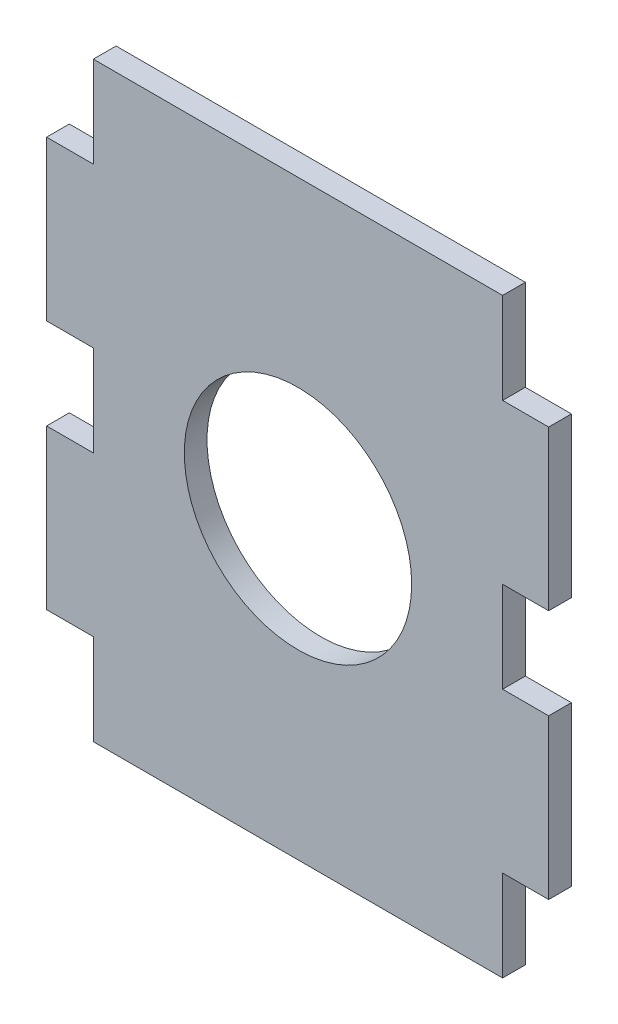
SolidWorks part; units mm, degrees
ref_plane "Front Plane" through (0, 0, 0) normal (0, 0, 1) x (1, 0, 0)
ref_plane "Top Plane" through (0, 0, 0) normal (0, 1, 0) x (1, 0, 0)
ref_plane "Right Plane" through (0, 0, 0) normal (1, 0, 0) x (0, 0, -1)
sketch "Sketch1" plane through (0, 0, 0) normal (0, 0, 1) x (1, 0, 0)
  line L1 (-56.6738, 356.0789) -> (0.4762, 356.0789)
  line L2 (-63.2032, 343.3789) -> (-63.2032, 321.1539)
  line L3 (-56.6738, 273.5289) -> (0.4762, 273.5289)
  line L4 (6.9085, 343.3789) -> (6.9085, 321.1539)
  line L6 (-56.6738, 347.6447) -> (-56.6738, 243.0666) construction
  line L7 (-63.2032, 308.4539) -> (-63.2032, 286.2289)
  line L8 (6.9085, 308.4539) -> (6.9085, 286.2289)
  line L9 (-63.2032, 343.3789) -> (-56.6738, 343.3789)
  line L10 (-56.6738, 356.0789) -> (-56.6738, 343.3789)
  line L11 (0.4762, 243.0666) -> (0.4762, 347.6447) construction
  line L14 (-63.2032, 286.2289) -> (-56.6738, 286.2289)
  line L15 (-56.6738, 273.5289) -> (-56.6738, 286.2289)
  line L16 (-63.2032, 308.4539) -> (-56.6738, 308.4539)
  line L18 (-63.2032, 321.1539) -> (-56.6738, 321.1539)
  line L19 (-56.6738, 308.4539) -> (-56.6738, 321.1539)
  line L22 (6.9085, 343.3789) -> (0.4762, 343.3789)
  line L23 (0.4762, 356.0789) -> (0.4762, 343.3789)
  line L27 (6.9085, 286.2289) -> (0.4762, 286.2289)
  line L28 (0.4762, 273.5289) -> (0.4762, 286.2289)
  line L29 (6.9085, 308.4539) -> (0.4762, 308.4539)
  line L31 (6.9085, 321.1539) -> (0.4762, 321.1539)
  line L32 (0.4762, 308.4539) -> (0.4762, 321.1539)
  circle A0 centre (-28.0988, 314.8039) radius 15.875
  dimension "D1" = 12.7
  dimension "D2" = 12.7
  dimension "D3" = 12.7
  dimension "D4" = 12.7
  dimension "D5" = 12.7
  dimension "D6" = 12.7
  dimension "D7" = 22.225
  dimension "D8" = 22.225
extrude "Boss-Extrude1" add sketch "Sketch1" against normal blind 3.175 contours L1 L23 L22 L4 L31 L32 L29 L8 L27 L28 L3 L15 L14 L7 L16 L19 L18 L2 L9 L10
